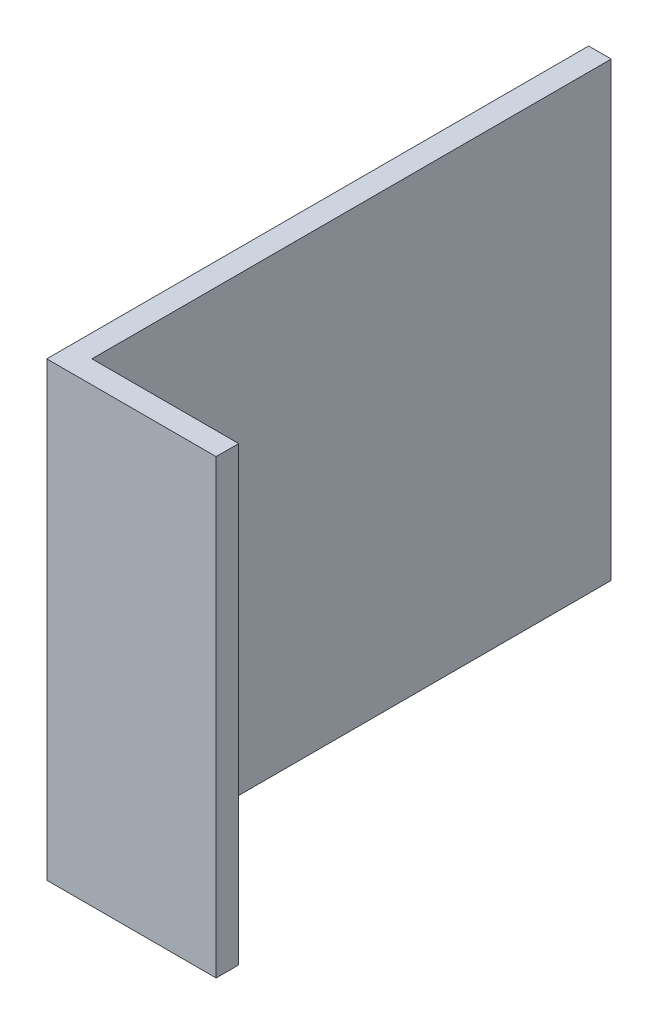
SolidWorks part; units mm, degrees
material "6061-T6 (SS)"
ref_plane "Front Plane" through (0, 0, 0) normal (0, 0, 1) x (1, 0, 0)
ref_plane "Top Plane" through (0, 0, 0) normal (0, 1, 0) x (1, 0, 0)
ref_plane "Right Plane" through (0, 0, 0) normal (1, 0, 0) x (0, 0, -1)
sketch "Sketch1" plane through (0, 0, 0) normal (0, 1, 0) x (1, 0, 0)
  line L0 (0, 76.2) -> (0, 0)
  line L1 (0, 0) -> (23.8125, 0)
  line L2 (3.175, 76.2) -> (3.175, 3.175)
  line L3 (0, 0) -> (101.6, 0) construction
  line L4 (0, 0) -> (0, 101.6) construction
  line L5 (0, 101.6) -> (101.6, 101.6) construction
  line L6 (101.6, 0) -> (101.6, 101.6) construction
  line L7 (3.175, 3.175) -> (23.8125, 3.175)
  line L8 (0, 76.2) -> (3.175, 76.2)
  line L9 (23.8125, 3.175) -> (23.8125, 0)
  dimension "D1" = 76.2
  dimension "D2" = 23.8125
  dimension "D3" = 101.6
  dimension "D4" = 101.6
  dimension "D5" = 3.175
extrude "Boss-Extrude1" add sketch "Sketch1" along normal blind 63.5
